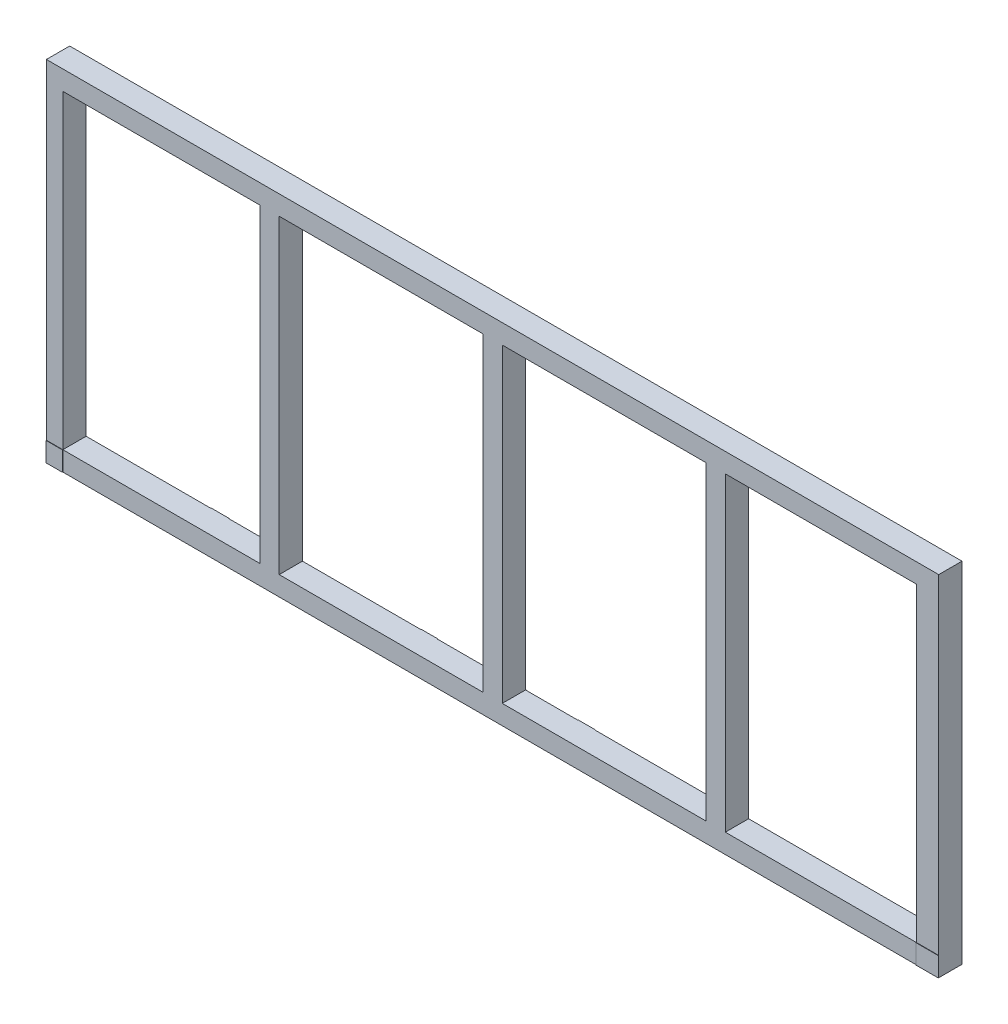
SolidWorks part; units mm, degrees
ref_plane "Front Plane" through (0, 0, 0) normal (0, 0, 1) x (1, 0, 0)
ref_plane "Top Plane" through (0, 0, 0) normal (0, 1, 0) x (1, 0, 0)
ref_plane "Right Plane" through (0, 0, 0) normal (1, 0, 0) x (0, 0, -1)
sketch "Sketch1" plane through (0, 0, 0) normal (0, 0, 1) x (1, 0, 0)
  line L0 (-550, 400) -> (-25, 400)
  line L1 (-1150, -450) -> (1150, -450)
  line L2 (-1150, -450) -> (-1150, 450)
  line L3 (-1150, 450) -> (1150, 450)
  line L4 (1150, -450) -> (1150, 450)
  line L5 (25, 400) -> (550, 400)
  line L6 (600, 400) -> (1092.3896, 400)
  line L7 (-1107.6104, -400) -> (-600, -400)
  line L8 (-1107.6104, -400) -> (-1107.6104, 400)
  line L9 (-1107.6104, 400) -> (-600, 400)
  line L10 (1092.3896, -400) -> (1092.3896, 400)
  line L11 (600, -400) -> (1092.3896, -400)
  line L13 (-600, -400) -> (-600, 400)
  line L15 (-550, -400) -> (-550, 400)
  line L16 (25, -400) -> (550, -400)
  line L17 (-550, -400) -> (-25, -400)
  line L19 (-25, -400) -> (-25, 400)
  line L21 (25, -400) -> (25, 400)
  line L25 (600, -400) -> (600, 400)
  line L27 (550, -400) -> (550, 400)
  point P0 (0, 0)
  point P6 (0, 0)
  point P17 (-575, 0)
  point P22 (0, 0)
  point P27 (575, -6.4314)
  point P32 (550, 0)
  dimension "D1" = 2300
  dimension "D2" = 900
  dimension "D3" = 800
  dimension "D4" = 2200
  dimension "D8" = 50
  dimension "D9" = 50
  dimension "D10" = 50
extrude "Boss-Extrude1" add sketch "Sketch1" along normal blind 60
sketch "Sketch2" plane through (0, 0, 60) normal (0, 0, 1) x (1, 0, 0)
  line L1 (-1107.6104, -400) -> (-1150, -400)
  line L2 (-1107.6104, -400) -> (-1107.6104, -450)
  line L3 (-1107.6104, -450) -> (-1150, -450)
  line L4 (-1150, -400) -> (-1150, -450)
  line L5 (1092.3896, -400) -> (1150, -400)
  line L6 (1092.3896, -400) -> (1092.3896, -450)
  line L7 (1092.3896, -450) -> (1150, -450)
  line L8 (1150, -400) -> (1150, -450)
extrude "Boss-Extrude2" add sketch "Sketch2" along normal blind 1
sketch "Sketch4" plane through (0, 0, 0) normal (0, 0, -1) x (-1, 0, 0)
  line L0 (-25, -400) -> (25, -400)
  line L1 (-25, -400) -> (-25, -450.4636)
  line L2 (25, -400) -> (25, -450.4636)
  line L3 (-25, -450.4636) -> (25, -450.4636)
extrude "Boss-Extrude4" add sketch "Sketch4" along normal blind 1
sketch "Sketch5" plane through (0, 0, 0) normal (0, 0, -1) x (-1, 0, 0)
  line L0 (-25, -400) -> (-550, -400) construction
  line L7 (-1150, -450) -> (-1150, 450) construction
  line L8 (-203.5183, -450) -> (-159.3017, -450)
  line L9 (-203.5183, -450) -> (-203.5183, -400)
  line L10 (-203.5183, -400) -> (-159.3017, -400)
  line L11 (-159.3017, -450) -> (-159.3017, -400)
  point P10 (-181.41, -425)
  dimension "D1" = 968.59
extrude "Boss-Extrude5" add sketch "Sketch5" along normal blind 1
sketch "Sketch6" plane through (0, 0, 0) normal (0, 0, -1) x (-1, 0, 0)
  line L7 (-1150, -450) -> (-1150, 450) construction
  line L8 (202.3661, -450) -> (244.8139, -450)
  line L9 (202.3661, -450) -> (202.3661, -400)
  line L10 (202.3661, -400) -> (244.8139, -400)
  line L11 (244.8139, -450) -> (244.8139, -400)
  point P10 (223.59, -425)
  dimension "D1" = 1373.59
extrude "Boss-Extrude6" add sketch "Sketch6" along normal blind 1
sketch "Sketch7" plane through (0, 0, 0) normal (0, 0, -1) x (-1, 0, 0)
  line L0 (1107.6104, -400) -> (600, -400) construction
  line L1 (740.2047, -400) -> (763.59, -400)
  line L3 (740.2047, -450) -> (763.59, -450)
  line L5 (1150, -450) -> (244.8139, -450) construction
  line L7 (1150, 450) -> (1150, -450) construction
  line L9 (740.2047, -450) -> (740.2047, -400)
  line L11 (786.9753, -450) -> (786.9753, -400)
  line L12 (763.59, -400) -> (786.9753, -400)
  line L13 (763.59, -450) -> (786.9753, -450)
  point P11 (763.59, -425)
  dimension "D1" = 386.41
extrude "Boss-Extrude7" add sketch "Sketch7" along normal blind 1
